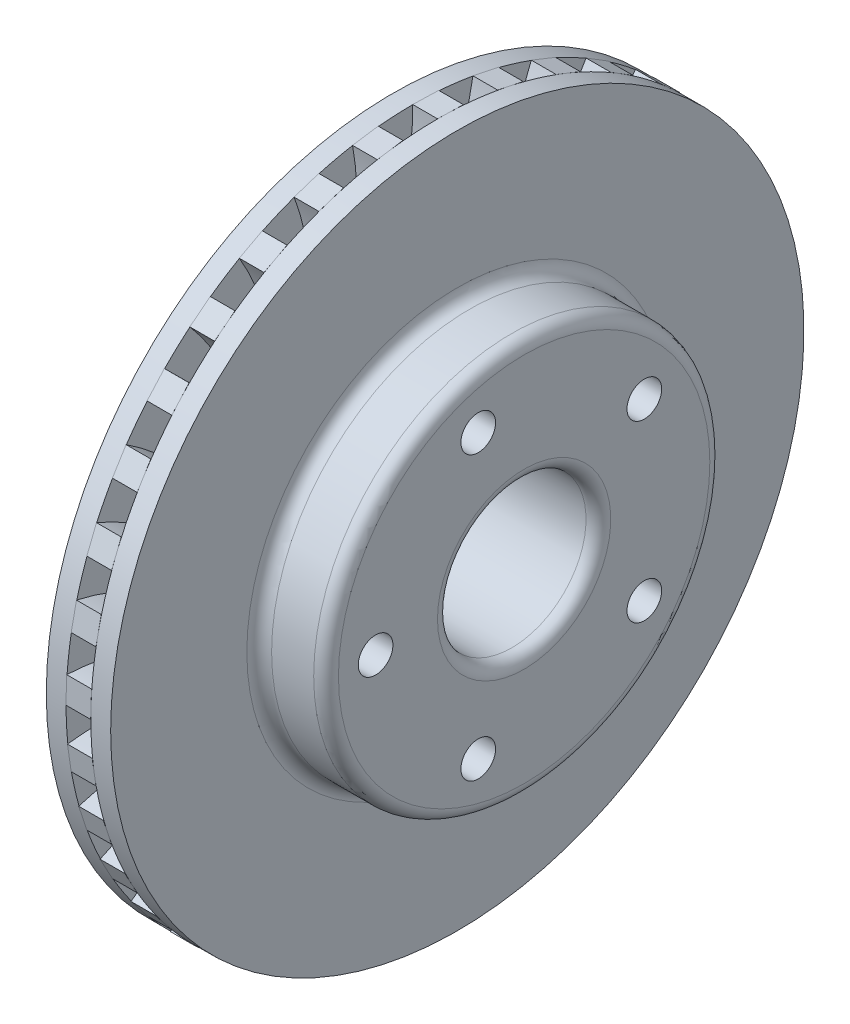
SolidWorks part; units mm, degrees
ref_plane "Front Plane" through (0, 0, 0) normal (0, 0, 1) x (1, 0, 0)
ref_plane "Top Plane" through (0, 0, 0) normal (0, 1, 0) x (1, 0, 0)
ref_plane "Right Plane" through (0, 0, 0) normal (1, 0, 0) x (0, 0, -1)
sketch "Sketch1" plane through (0, 0, 0) normal (0, 0, 1) x (1, 0, 0)
  line L0 (-87.2083, 0) -> (93.1667, 0) construction
  line L1 (13, 140) -> (13, 85)
  line L2 (18, 80) -> (35, 80)
  line L3 (40, 75) -> (40, 35)
  line L4 (35, 30) -> (-35, 30)
  line L5 (-40, 35) -> (-40, 75)
  line L6 (-35, 80) -> (-18, 80)
  line L7 (-13, 85) -> (-13, 140)
  line L8 (-13, 140) -> (-5, 140)
  line L9 (-5, 140) -> (-5, 55)
  line L10 (-10, 50) -> (-25, 50)
  line L11 (-30, 45) -> (-30, 40)
  line L12 (-25, 35) -> (15, 35)
  line L13 (20, 40) -> (20, 50)
  line L14 (15, 55) -> (5, 55)
  line L15 (5, 55) -> (5, 140)
  line L16 (5, 140) -> (13, 140)
  line L17 (0, 0) -> (0, 165.2158) construction
  arc A0 (-25, 50) -> (-30, 45) centre (-25, 45) ccw
  arc A1 (-5, 55) -> (-10, 50) centre (-10, 55) cw
  arc A2 (-18, 80) -> (-13, 85) centre (-18, 85) ccw
  arc A3 (-40, 75) -> (-35, 80) centre (-35, 75) cw
  arc A4 (-35, 30) -> (-40, 35) centre (-35, 35) cw
  arc A5 (40, 35) -> (35, 30) centre (35, 35) cw
  arc A6 (35, 80) -> (40, 75) centre (35, 75) cw
  arc A7 (20, 50) -> (15, 55) centre (15, 50) ccw
  arc A8 (13, 85) -> (18, 80) centre (18, 85) ccw
  arc A9 (15, 35) -> (20, 40) centre (15, 40) ccw
  arc A10 (-30, 40) -> (-25, 35) centre (-25, 40) ccw
  point P22 (0, 30)
  point P28 (-13, 80)
  point P33 (-40, 30)
  point P36 (40, 30)
  point P43 (13, 80)
  dimension "D13" = 5
  dimension "D14" = 5
  dimension "D1" = 26
  dimension "D2" = 140
  dimension "D3" = 80
  dimension "D4" = 5
  dimension "D5" = 8
  dimension "D6" = 30
  dimension "D7" = 20
  dimension "D8" = 80
  dimension "D9" = 13
  dimension "D10" = 15
  dimension "D11" = 20
  dimension "D12" = 30
revolve "Revolve1" add sketch "Sketch1" angle 360 about L0
sketch "Sketch3" plane through (-5, 0, 0) normal (1, 0, 0) x (0, 0, -1)
  line L0 (-0.0008, 140.0622) -> (10.4992, 139.7492)
  line L1 (-13.9534, 78.7737) -> (-21.2682, 77.1211)
  arc A2 (-0.0008, 140.0622) -> (-21.2682, 77.1211) centre (-99.9926, 138.7852) cw
  arc A4 (10.4992, 139.7492) -> (-13.9534, 78.7737) centre (-89.3918, 144.4171) cw
extrude "Boss-Extrude1" add sketch "Sketch3" along normal blind 10
pattern_circular "CirPattern1" count 36 over 360 about axis through (0, 0, 0) along (1, 0, 0) of "Boss-Extrude1"
sketch "Sketch4" plane through (-40, 0, 0) normal (-1, 0, 0) x (0, 0, 1)
  circle A0 centre (0, 0) radius 60 construction
  circle A1 centre (60, 0) radius 7
  circle A2 centre (18.541, -57.0634) radius 7
  circle A3 centre (-48.541, -35.2671) radius 7
  circle A4 centre (-48.541, 35.2671) radius 7
  circle A5 centre (18.541, 57.0634) radius 7
  point P16 (0, 0)
  dimension "D1" = 120
  dimension "D2" = 14
  dimension "D3" = 5
extrude "Cut-Extrude1" cut sketch "Sketch4" against normal up to surface and the other way through all up to face at (40, 0, 75)
